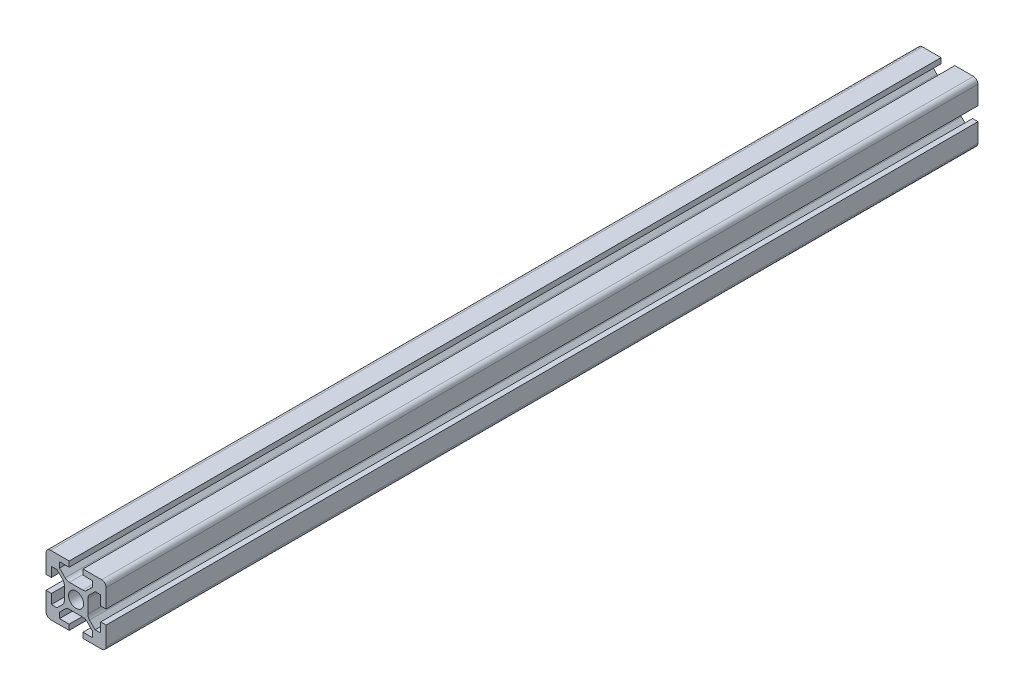
SolidWorks part; units mm, degrees
ref_plane "Alzado" through (0, 0, 0) normal (0, 0, 1) x (1, 0, 0)
ref_plane "Planta" through (0, 0, 0) normal (0, 1, 0) x (1, 0, 0)
ref_plane "Vista lateral" through (0, 0, 0) normal (1, 0, 0) x (0, 0, -1)
sketch "Croquis1" plane through (0, 0, 0) normal (0, 0, 1) x (1, 0, 0)
  line L0 (0, 0) -> (-10, 0) construction
  line L1 (-10, 0) -> (-10, 10) construction
  line L2 (-10, 10) -> (0, 10) construction
  line L3 (0, 10) -> (0, 0) construction
  line L4 (-10, 8.5) -> (-10, 2.3)
  line L5 (-8.2, 2.3) -> (-8.2, 5.5)
  line L6 (-6.3485, 5.5) -> (-4.4858, 3.6373)
  line L7 (-10, 10) -> (0, 0) construction
  line L8 (-3.9, 2.223) -> (-3.9, 0)
  line L9 (-8.2, 5.5) -> (-6.3485, 5.5)
  line L14 (-10, 2.3) -> (-8.2, 2.3)
  line L15 (-2.223, 3.9) -> (0, 3.9)
  line L16 (-5.5, 6.3485) -> (-3.6373, 4.4858)
  line L17 (-5.5, 8.2) -> (-5.5, 6.3485)
  line L18 (-2.3, 10) -> (-2.3, 8.2)
  line L19 (-2.3, 8.2) -> (-5.5, 8.2)
  line L20 (-8.5, 10) -> (-2.3, 10)
  line L21 (8.5, 10) -> (2.3, 10)
  line L22 (2.3, 10) -> (2.3, 8.2)
  line L23 (2.3, 8.2) -> (5.5, 8.2)
  line L24 (5.5, 8.2) -> (5.5, 6.3485)
  line L25 (5.5, 6.3485) -> (3.6373, 4.4858)
  line L26 (2.223, 3.9) -> (0, 3.9)
  line L27 (3.9, 2.223) -> (3.9, 0)
  line L28 (6.3485, 5.5) -> (4.4858, 3.6373)
  line L29 (8.2, 5.5) -> (6.3485, 5.5)
  line L30 (8.2, 2.3) -> (8.2, 5.5)
  line L31 (10, 2.3) -> (8.2, 2.3)
  line L32 (10, 8.5) -> (10, 2.3)
  line L33 (10, -8.5) -> (10, -2.3)
  line L34 (10, -2.3) -> (8.2, -2.3)
  line L35 (8.2, -2.3) -> (8.2, -5.5)
  line L36 (8.2, -5.5) -> (6.3485, -5.5)
  line L37 (6.3485, -5.5) -> (4.4858, -3.6373)
  line L38 (3.9, -2.223) -> (3.9, 0)
  line L39 (2.223, -3.9) -> (0, -3.9)
  line L40 (5.5, -6.3485) -> (3.6373, -4.4858)
  line L41 (5.5, -8.2) -> (5.5, -6.3485)
  line L42 (2.3, -8.2) -> (5.5, -8.2)
  line L43 (2.3, -10) -> (2.3, -8.2)
  line L44 (8.5, -10) -> (2.3, -10)
  line L45 (-8.5, -10) -> (-2.3, -10)
  line L46 (-2.3, -10) -> (-2.3, -8.2)
  line L47 (-2.3, -8.2) -> (-5.5, -8.2)
  line L48 (-5.5, -8.2) -> (-5.5, -6.3485)
  line L49 (-5.5, -6.3485) -> (-3.6373, -4.4858)
  line L50 (-2.223, -3.9) -> (0, -3.9)
  line L51 (-3.9, -2.223) -> (-3.9, 0)
  line L52 (-6.3485, -5.5) -> (-4.4858, -3.6373)
  line L53 (-8.2, -5.5) -> (-6.3485, -5.5)
  line L54 (-8.2, -2.3) -> (-8.2, -5.5)
  line L55 (-10, -2.3) -> (-8.2, -2.3)
  line L56 (-10, -8.5) -> (-10, -2.3)
  arc A0 (-8.5, 10) -> (-10, 8.5) centre (-8.5, 8.5) ccw
  arc A1 (0, 2.5) -> (-2.5, 0) centre (0, 0) ccw
  arc A2 (-3.9, 2.223) -> (-4.4858, 3.6373) centre (-5.9, 2.223) ccw
  arc A3 (-2.223, 3.9) -> (-3.6373, 4.4858) centre (-2.223, 5.9) cw
  arc A4 (2.223, 3.9) -> (3.6373, 4.4858) centre (2.223, 5.9) ccw
  arc A5 (2.5, 0) -> (0, 2.5) centre (0, 0) ccw
  arc A6 (3.9, 2.223) -> (4.4858, 3.6373) centre (5.9, 2.223) cw
  arc A7 (10, 8.5) -> (8.5, 10) centre (8.5, 8.5) ccw
  arc A8 (3.9, -2.223) -> (4.4858, -3.6373) centre (5.9, -2.223) ccw
  arc A9 (0, -2.5) -> (2.5, 0) centre (0, 0) ccw
  arc A10 (2.223, -3.9) -> (3.6373, -4.4858) centre (2.223, -5.9) cw
  arc A11 (8.5, -10) -> (10, -8.5) centre (8.5, -8.5) ccw
  arc A12 (-2.223, -3.9) -> (-3.6373, -4.4858) centre (-2.223, -5.9) ccw
  arc A13 (-2.5, 0) -> (0, -2.5) centre (0, 0) ccw
  arc A14 (-3.9, -2.223) -> (-4.4858, -3.6373) centre (-5.9, -2.223) cw
  arc A15 (-10, -8.5) -> (-8.5, -10) centre (-8.5, -8.5) ccw
  point P92 (0, 0)
  dimension "D3" = 3
  dimension "D9" = 2.5
  dimension "D10" = 2
  dimension "D2" = 10
  dimension "D4" = 6.2
  dimension "D5" = 1.8
  dimension "D6" = 0.6
  dimension "D7" = 6.1
  dimension "D8" = 5.5
  dimension "D11" = 4
extrude "Saliente-Extruir1" add sketch "Croquis1" along normal blind 290
